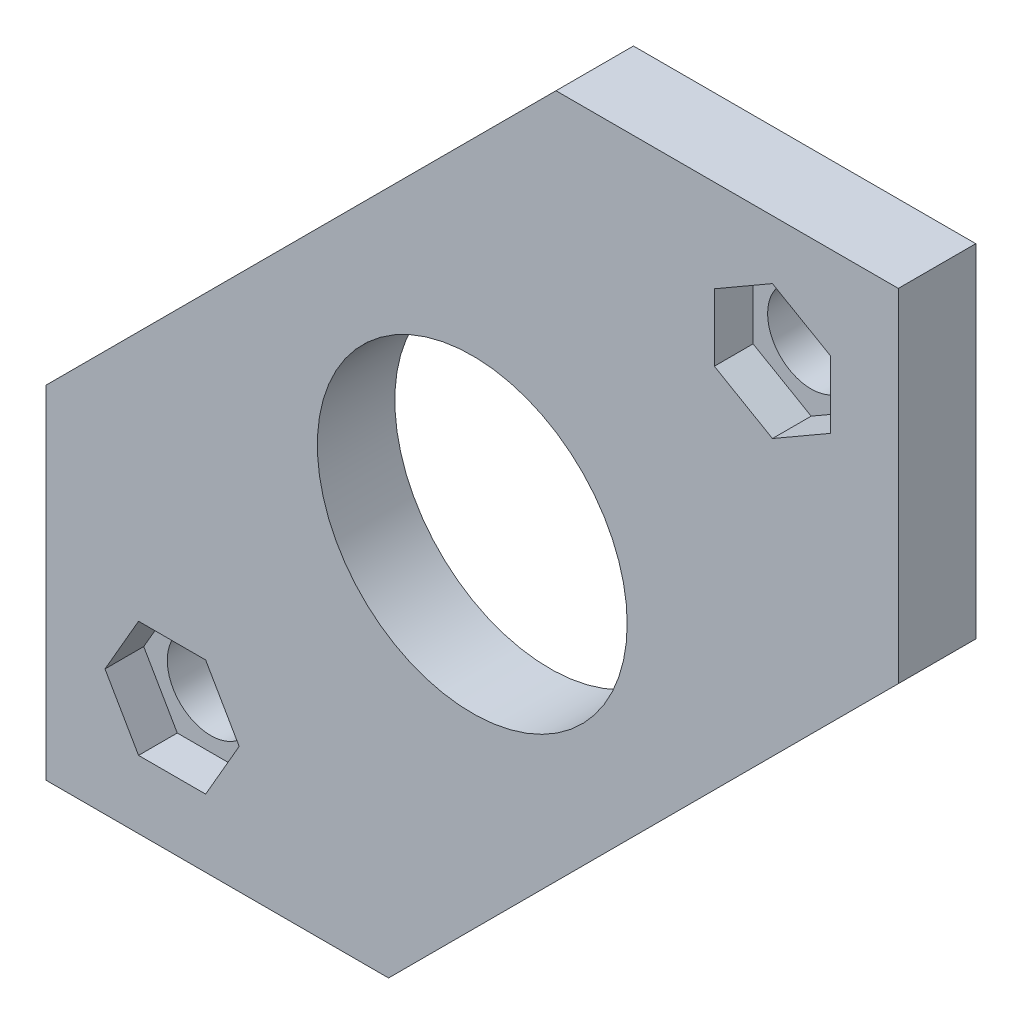
SolidWorks part; units mm, degrees
ref_plane "Top Plane" through (0, 0, 0) normal (0, 0, 1) x (1, 0, 0)
ref_plane "Right Plane" through (0, 0, 0) normal (0, 1, 0) x (1, 0, 0)
ref_plane "Front Plane" through (0, 0, 0) normal (1, 0, 0) x (0, 0, -1)
sketch "Sketch1" plane through (0, 0, 0) normal (0, 0, 1) x (1, 0, 0)
  line L0 (-4.3223, -22) -> (-22, -22)
  line L1 (-22, -22) -> (28, -22) construction
  line L2 (-22, -22) -> (-22, -4.3223)
  line L3 (-22, 22) -> (-22, -22) construction
  line L4 (4.3223, 22) -> (22, 22)
  line L5 (28, 22) -> (-22, 22) construction
  line L6 (22, 22) -> (22, 4.3223)
  line L7 (22, 4.3223) -> (-4.3223, -22)
  line L8 (-22, -4.3223) -> (4.3223, 22)
  circle A0 centre (0, 0) radius 8
  circle A1 centre (0, 0) radius 8 construction
  circle A2 centre (-15.5, -15.5) radius 2.25
  circle A3 centre (15.5, 15.5) radius 2.25
  circle A4 centre (-15.5, -15.5) radius 2.25 construction
  dimension "D1" = 25
extrude "Boss-Extrude1" add sketch "Sketch1" along normal blind 4
sketch "Sketch2" plane through (0, 0, 4) normal (0, 0, 1) x (1, 0, 0)
  line L0 (-18.9641, -15.5) -> (-17.2321, -18.5)
  line L1 (-17.2321, -18.5) -> (-13.7679, -18.5)
  line L2 (-13.7679, -18.5) -> (-12.0359, -15.5)
  line L3 (-12.0359, -15.5) -> (-13.7679, -12.5)
  line L4 (-13.7679, -12.5) -> (-17.2321, -12.5)
  line L5 (-17.2321, -12.5) -> (-18.9641, -15.5)
  line L6 (-8.8388, 8.8388) -> (8.8388, -8.8388) construction
  line L7 (4.3223, 22) -> (-22, -4.3223) construction
  line L8 (-4.3223, -22) -> (22, 4.3223) construction
  line L9 (12.5, 13.7679) -> (12.5, 17.2321)
  line L10 (15.5, 12.0359) -> (12.5, 13.7679)
  line L11 (18.5, 13.7679) -> (15.5, 12.0359)
  line L12 (18.5, 17.2321) -> (18.5, 13.7679)
  line L13 (15.5, 18.9641) -> (18.5, 17.2321)
  line L14 (12.5, 17.2321) -> (15.5, 18.9641)
  circle A0 centre (-15.5, -15.5) radius 3.4641 construction
  dimension "D1" = 6
extrude "Cut-Extrude1" cut sketch "Sketch2" against normal blind 2
